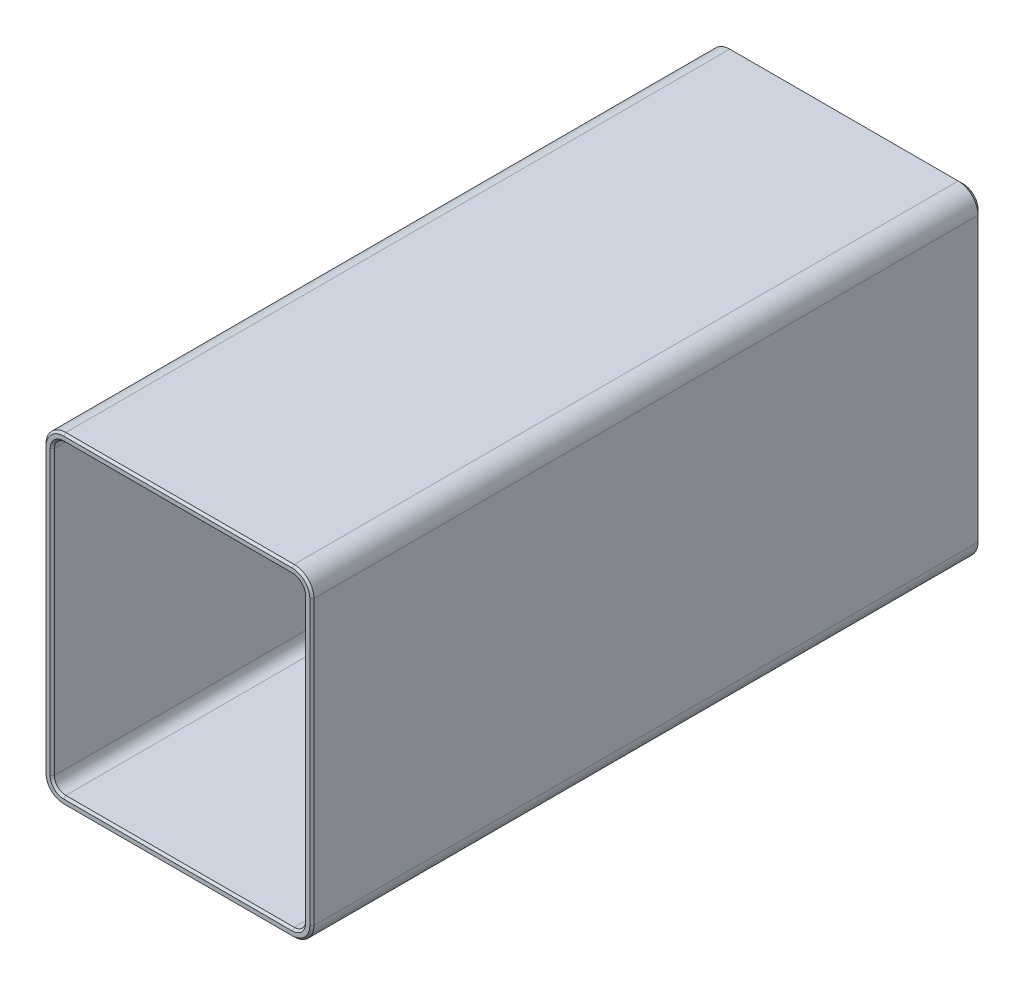
SolidWorks part; units mm, degrees
ref_plane "Front" through (0, 0, 0) normal (0, 0, 1) x (1, 0, 0)
ref_plane "Top" through (0, 0, 0) normal (0, 1, 0) x (1, 0, 0)
ref_plane "Right" through (0, 0, 0) normal (1, 0, 0) x (0, 0, -1)
sketch "Sketch1" plane through (0, 0, 0) normal (0, 0, 1) x (1, 0, 0)
  line L1 (-21.95, -31) -> (21.95, -31)
  line L2 (-25.75, -27.2) -> (-25.75, 27.2)
  line L3 (-21.95, 31) -> (21.95, 31)
  line L4 (25.75, -27.2) -> (25.75, 27.2)
  line L5 (-25.75, -31) -> (25.75, 31) construction
  line L6 (-25.75, 31) -> (25.75, -31) construction
  arc A0 (21.95, 31) -> (25.75, 27.2) centre (21.95, 27.2) cw
  arc A1 (21.95, -31) -> (25.75, -27.2) centre (21.95, -27.2) ccw
  arc A2 (-21.95, -31) -> (-25.75, -27.2) centre (-21.95, -27.2) cw
  arc A3 (-25.75, 27.2) -> (-21.95, 31) centre (-21.95, 27.2) cw
  point P0 (0, 0)
  dimension "D3" = 3.8
  dimension "D1" = 51.5
  dimension "D2" = 62
extrude "Walls" add sketch "Sketch1" along normal blind 129 thin thin type one direction reverse wall 1.6
sketch "Sketch2" plane through (0, 0, 0) normal (0, 0, -1) x (-1, 0, 0)
  line L4 (-25.75, 27.2) -> (-25.75, -27.2)
  line L5 (-21.95, -31) -> (21.95, -31)
  line L6 (25.75, -27.2) -> (25.75, 27.2)
  line L7 (21.95, 31) -> (-21.95, 31)
  line L8 (-25.75, 27.2) -> (-25.75, -27.2)
  line L9 (-21.95, -31) -> (21.95, -31)
  line L10 (25.75, -27.2) -> (25.75, 27.2)
  line L11 (21.95, 31) -> (-21.95, 31)
  arc A4 (-21.95, 31) -> (-25.75, 27.2) centre (-21.95, 27.2) ccw
  arc A5 (-25.75, -27.2) -> (-21.95, -31) centre (-21.95, -27.2) ccw
  arc A6 (21.95, -31) -> (25.75, -27.2) centre (21.95, -27.2) ccw
  arc A7 (25.75, 27.2) -> (21.95, 31) centre (21.95, 27.2) ccw
  arc A8 (-21.95, 31) -> (-25.75, 27.2) centre (-21.95, 27.2) ccw
  arc A9 (-25.75, -27.2) -> (-21.95, -31) centre (-21.95, -27.2) ccw
  arc A10 (21.95, -31) -> (25.75, -27.2) centre (21.95, -27.2) ccw
  arc A11 (25.75, 27.2) -> (21.95, 31) centre (21.95, 27.2) ccw
  dimension "D1" = 0
extrude "Floor" add sketch "Sketch2" against normal blind 2.6
chamfer "Bottom Chamfers" distance 1 angle 45 8 edges at (0, 31, 0) (-24.637, 29.887, 0) (-25.75, 0, 0) (-24.637, -29.887, 0) (0, -31, 0) (24.637, -29.887, 0) (25.75, 0, 0) (24.637, 29.887, 0)
chamfer "Top Chamfers" distance 0.4 angle 45 16 edges at (-23.5056, 28.7556, 129) (-24.15, 0, 129) (-23.5056, -28.7556, 129) (0, -29.4, 129) (23.5056, -28.7556, 129) (24.15, 0, 129) (23.5056, 28.7556, 129) (0, 29.4, 129) (25.75, 0, 129) (24.637, -29.887, 129) (0, -31, 129) (-24.637, -29.887, 129) (-25.75, 0, 129) (-24.637, 29.887, 129) (0, 31, 129) (24.637, 29.887, 129)
fillet "Inside Bottom Fillet" radius 1 8 edges at (24.15, 0, 2.6) (23.5056, -28.7556, 2.6) (0, -29.4, 2.6) (-23.5056, -28.7556, 2.6) (-24.15, 0, 2.6) (-23.5056, 28.7556, 2.6) (0, 29.4, 2.6) (23.5056, 28.7556, 2.6)
equation "\"Width\" = 51.5mm"
equation "\"Length\" = 62mm"
equation "\"Depth\"= 129mm"
equation "\"D1@Sketch1\"=\"Width\""
equation "\"D2@Sketch1\"=\"Length\""
equation "\"D1@Walls\"=\"Depth\""
